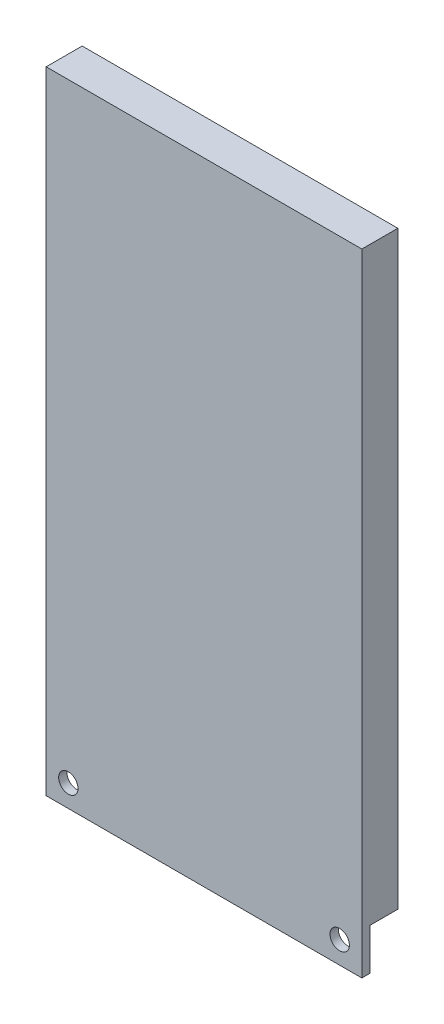
SolidWorks part; units mm, degrees
ref_plane "Plan de face" through (0, 0, 0) normal (0, 0, 1) x (1, 0, 0)
ref_plane "Plan de dessus" through (0, 0, 0) normal (0, 1, 0) x (1, 0, 0)
ref_plane "Plan de droite" through (0, 0, 0) normal (1, 0, 0) x (0, 0, -1)
sketch "Esquisse1" plane through (0, 0, 0) normal (0, 0, 1) x (1, 0, 0)
  line L1 (0, 0) -> (57, 0)
  line L2 (0, 0) -> (0, 114)
  line L3 (0, 114) -> (57, 114)
  line L4 (57, 0) -> (57, 114)
  dimension "D1" = 57
  dimension "D2" = 114
extrude "Boss.-Extru.1" add sketch "Esquisse1" along normal blind 1.5
sketch "Esquisse3" plane through (0, 0, 0) normal (0, 0, -1) x (-1, 0, 0)
  line L0 (0, 114) -> (0, 0) construction
  line L1 (-57, 114) -> (0, 114)
  line L2 (-57, 114) -> (-57, 7.5)
  line L3 (-57, 7.5) -> (0, 7.5)
  line L4 (0, 114) -> (0, 7.5)
  line L5 (0, 0) -> (-57, 0) construction
  line L6 (-57, 0) -> (-57, 114) construction
  line L8 (-55, 112) -> (-2, 112)
  line L9 (-55, 112) -> (-55, 9.5)
  line L10 (-55, 9.5) -> (-2, 9.5)
  line L11 (-2, 112) -> (-2, 9.5)
  circle A0 centre (-4, 4) radius 1.75
  circle A1 centre (-53, 4) radius 1.75
  dimension "D2" = 3.5
  dimension "D3" = 3.5
  dimension "D1" = 7.5
  dimension "D4" = 3.5
  dimension "D5" = 3.5
  dimension "D6" = 49
  dimension "D7" = 4
  dimension "D8" = 2
  dimension "D9" = 2
  dimension "D10" = 2
  dimension "D11" = 2
extrude "Boss.-Extru.2" add sketch "Esquisse3" along normal blind 5
sketch "Esquisse4" plane through (0, 0, -5) normal (0, 0, -1) x (-1, 0, 0)
  circle A0 centre (-4, 4) radius 1.75
  circle A1 centre (-53, 4) radius 1.75
extrude "Enlèv. mat.-Extru.1" cut sketch "Esquisse4" against normal blind 12
